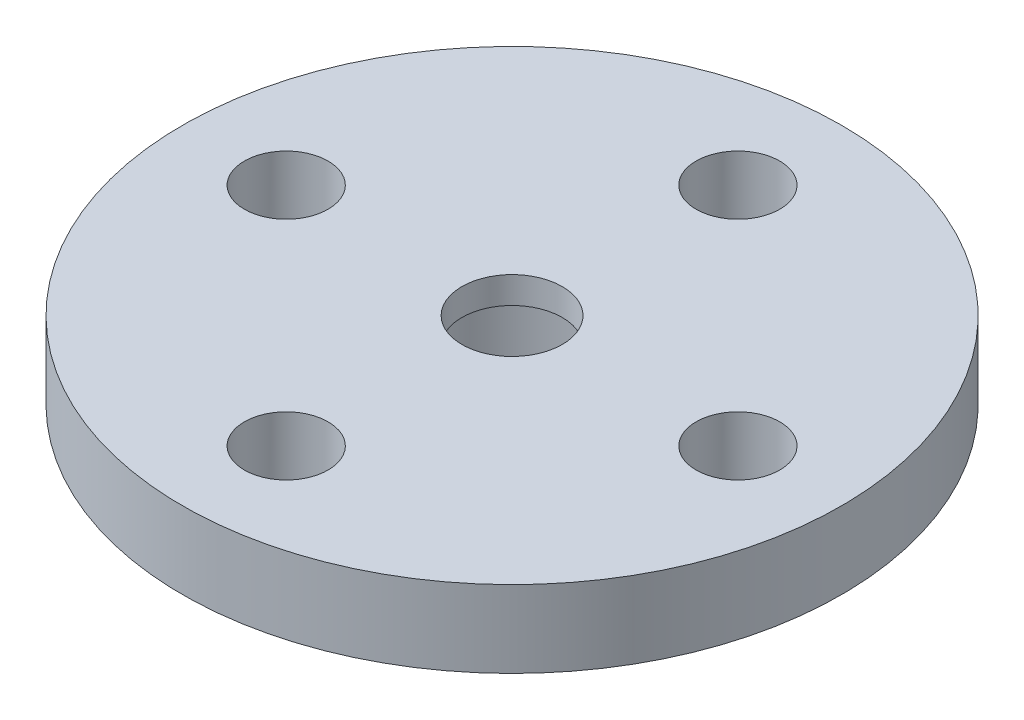
SolidWorks part; units mm, degrees
material "7075-T6 (SN)"
ref_plane "前视基准面" through (0, 0, 0) normal (0, 0, 1) x (1, 0, 0)
ref_plane "上视基准面" through (0, 0, 0) normal (0, 1, 0) x (1, 0, 0)
ref_plane "右视基准面" through (0, 0, 0) normal (1, 0, 0) x (0, 0, -1)
sketch "草图1" plane through (0, 0, 0) normal (0, 0, 1) x (1, 0, 0)
  line L0 (0, 0) -> (0, 8974.8117) construction
  line L1 (1.5, 0) -> (9.85, 0)
  line L2 (9.85, 0) -> (9.85, -2.3)
  line L3 (9.85, -2.3) -> (4.4, -2.3)
  line L4 (4.4, -2.3) -> (4.4, -4.3)
  line L5 (4.4, -4.3) -> (3, -4.3)
  line L6 (3, -4.3) -> (3, -0.8)
  line L7 (3, -0.8) -> (1.5, -0.8)
  line L8 (1.5, -0.8) -> (1.5, 0)
  dimension "D1" = 4.3
  dimension "D2" = 19.7
  dimension "D3" = 3
  dimension "D4" = 2.3
  dimension "D5" = 8.8
  dimension "D6" = 3.5
  dimension "D7" = 6
revolve "旋转1" add sketch "草图1" angle 360 about L0
sketch "草图2" plane through (0, 0, 0) normal (0, 1, 0) x (1, 0, 0)
  circle A0 centre (0, 0) radius 6.75 construction
  circle A1 centre (0, 6.75) radius 1.5 construction
  circle A2 centre (6.75, 0) radius 1.5 construction
  circle A3 centre (0, -6.75) radius 1.5 construction
  circle A4 centre (-6.75, 0) radius 1.5 construction
  dimension "D1" = 3
  dimension "D2" = 13.5
hole_wizard "M3 螺纹孔1" positions "草图5" profile "草图6" tap size "M3" standard "GB" end condition through all
sketch "草图5" plane through (0, 0, 0) normal (0, 1, 0) x (1, 0, 0)
  point P0 (0, 6.75)
  point P3 (6.75, 0)
  point P6 (0, -6.75)
  point P9 (-6.75, 0)
sketch "草图6" plane through (0, 0, -6.75) normal (1, 0, 0) x (0, 0, 1)
  line L0 (0, 0) -> (0, 4.3)
  line L1 (0, 4.3) -> (1.25, 4.3)
  line L2 (1.25, 4.3) -> (1.25, 0)
  line L5 (1.25, 0) -> (0, 0)
  line L11 (0, -6.35) -> (0, 107.95) construction
  dimension "通孔螺纹孔钻头直径" = 2.5
  dimension "通孔螺纹孔钻头深度" = 4.3
cosmetic thread "孔螺蚊线1"
cosmetic thread "孔螺蚊线2"
cosmetic thread "孔螺蚊线3"
cosmetic thread "孔螺蚊线4"
